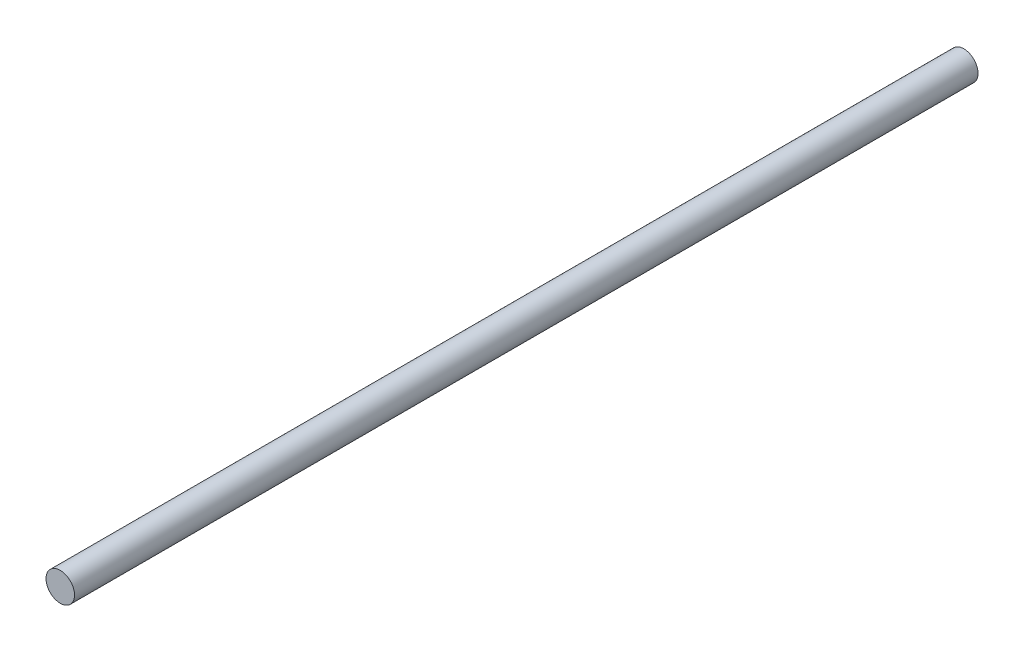
SolidWorks part; units mm, degrees
ref_plane "Front Plane" through (0, 0, 0) normal (0, 0, 1) x (1, 0, 0)
ref_plane "Top Plane" through (0, 0, 0) normal (0, 1, 0) x (1, 0, 0)
ref_plane "Right Plane" through (0, 0, 0) normal (1, 0, 0) x (0, 0, -1)
sketch "Sketch1" plane through (0, 0, 0) normal (0, 0, 1) x (1, 0, 0)
  circle A0 centre (0, 0) radius 15
  dimension "D1" = 30
extrude "Boss-Extrude1" add sketch "Sketch1" along normal blind 950 contours A0
